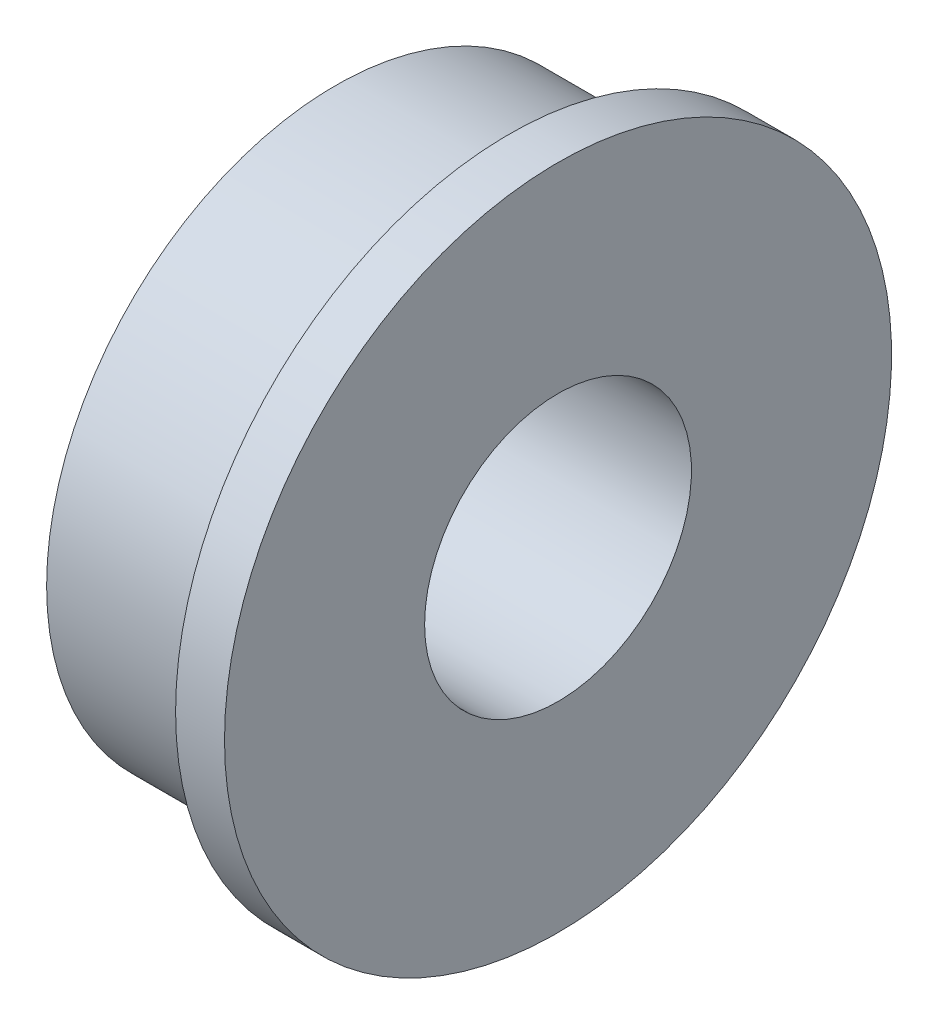
SolidWorks part; units mm, degrees
ref_plane "前视基准面" through (0, 0, 0) normal (0, 0, 1) x (1, 0, 0)
ref_plane "上视基准面" through (0, 0, 0) normal (0, 1, 0) x (1, 0, 0)
ref_plane "右视基准面" through (0, 0, 0) normal (1, 0, 0) x (0, 0, -1)
sketch "草图1" plane through (0, 0, 0) normal (0, 0, 1) x (1, 0, 0)
  line L0 (-46.8649, 0) -> (78, 0) construction
  line L1 (0, 7.5) -> (0, 3)
  line L2 (0, 7.5) -> (-1.1, 7.5)
  line L3 (-1.1, 7.5) -> (-1.1, 6.5)
  line L4 (-1.1, 6.5) -> (-5, 6.5)
  line L5 (-5, 6.5) -> (-5, 3)
  line L6 (-5, 3) -> (0, 3)
  dimension "D1" = 6
  dimension "D2" = 13
  dimension "D3" = 15
  dimension "D4" = 5
  dimension "D5" = 1.1
revolve "旋转1" add sketch "草图1" angle 360 about L0
